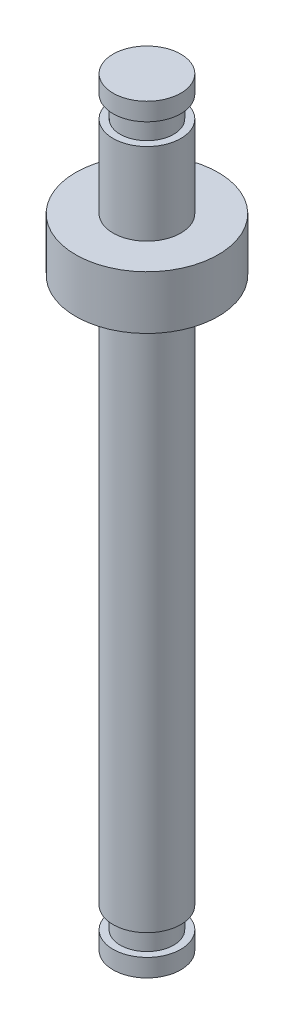
SolidWorks part; units mm, degrees
ref_plane "Front Plane" through (0, 0, 0) normal (0, 0, 1) x (1, 0, 0)
ref_plane "Top Plane" through (0, 0, 0) normal (0, 1, 0) x (1, 0, 0)
ref_plane "Right Plane" through (0, 0, 0) normal (1, 0, 0) x (0, 0, -1)
ref_plane "Plane1" through (0, 0, 0) normal (0, 0, -1) x (-1, 0, 0)
sketch "Sketch1" plane through (0, 0, 0) normal (0, 0, -1) x (-1, 0, 0)
  line L0 (-1.9, -35.3) -> (0, -35.3)
  line L1 (0, -35.3) -> (0, 7.3)
  line L2 (0, 7.3) -> (-1.9, 7.3)
  line L3 (-1.9, 7.3) -> (-1.9, 6.3)
  line L4 (-1.9, 6.3) -> (-1.5, 6.3)
  line L5 (-1.5, 6.3) -> (-1.5, 5.1)
  line L6 (-1.5, 5.1) -> (-1.9, 5.1)
  line L7 (-1.9, 5.1) -> (-1.9, 0.5)
  line L8 (-1.9, 0.5) -> (-4, 0.5)
  line L9 (-4, 0.5) -> (-4, -2.5)
  line L10 (-4, -2.5) -> (-1.9, -2.5)
  line L11 (-1.9, -2.5) -> (-1.9, -33.1)
  line L12 (-1.9, -33.1) -> (-1.5, -33.1)
  line L13 (-1.5, -33.1) -> (-1.5, -34.3)
  line L14 (-1.5, -34.3) -> (-1.9, -34.3)
  line L15 (-1.9, -34.3) -> (-1.9, -35.3)
  line L16 (0, -35.3) -> (0, 7.3) construction
  dimension "D1" = 42.6
  dimension "D2" = 1.2
  dimension "D3" = 0.4
  dimension "D4" = 1.9
  dimension "D5" = 3
  dimension "D6" = 2.1
  dimension "D7" = 1.2
  dimension "D8" = 35.3
  dimension "D9" = 1.9
  dimension "D10" = 0.5
  dimension "D11" = 6.3
  dimension "D12" = 33.1
revolve "Revolve1" add sketch "Sketch1" angle 360 about L16
